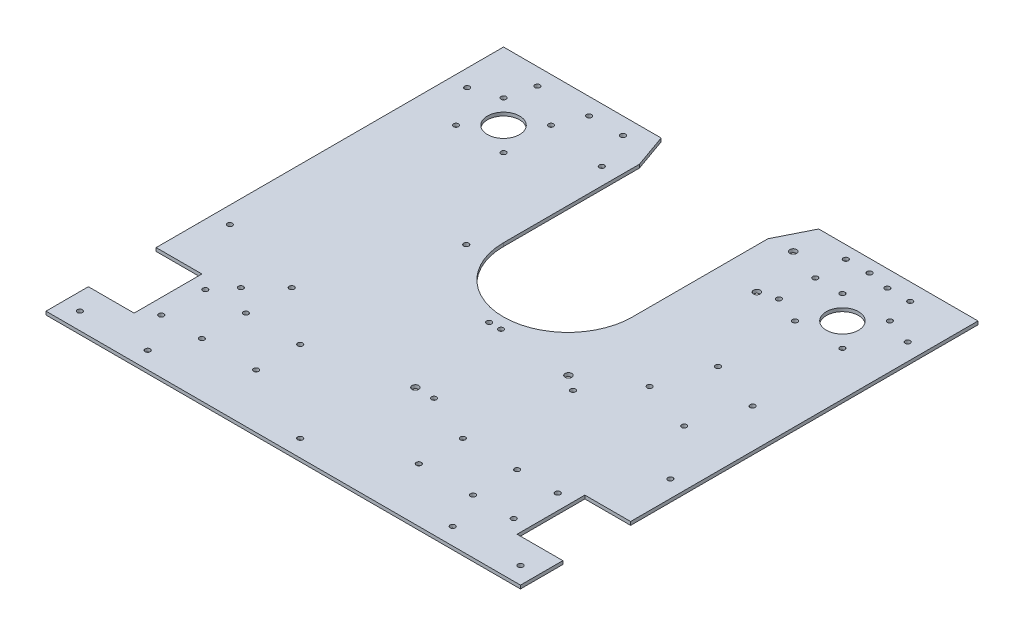
SolidWorks part; units mm, degrees
ref_plane "Plan de face" through (0, 0, 0) normal (0, 0, 1) x (1, 0, 0)
ref_plane "Plan de dessus" through (0, 0, 0) normal (0, 1, 0) x (1, 0, 0)
ref_plane "Plan de droite" through (0, 0, 0) normal (1, 0, 0) x (0, 0, -1)
sketch "Esquisse1" plane through (0, 0, 0) normal (0, 1, 0) x (1, 0, 0)
  line L0 (215.2266, 224.3116) -> (-64.7734, 224.3116)
  line L1 (-64.7734, 224.3116) -> (-64.7734, 19.3116)
  line L2 (-64.7734, 19.3116) -> (-37.7734, 19.3116)
  line L3 (-37.7734, 19.3116) -> (-37.7734, -20.6884)
  line L4 (-37.7734, -20.6884) -> (-64.7734, -20.6884)
  line L5 (-64.7734, -20.6884) -> (-64.7734, -45.6884)
  line L6 (-64.7734, -45.6884) -> (215.2266, -45.6884)
  line L7 (215.2266, -45.6884) -> (215.2266, -20.6884)
  line L8 (215.2266, -20.6884) -> (188.2266, -20.6884)
  line L9 (188.2266, -20.6884) -> (188.2266, 19.3116)
  line L10 (188.2266, 19.3116) -> (215.2266, 19.3116)
  line L11 (215.2266, 19.3116) -> (215.2266, 224.3116)
  line L12 (3.9048, -0.6884) -> (149.2216, -0.6884) construction
  line L13 (75.2266, -25.6884) -> (75.2266, 10.3116) construction
  circle A0 centre (27.2266, 12.3116) radius 1.5
  circle A1 centre (27.2266, -13.6884) radius 1.5
  circle A2 centre (123.2266, -13.6884) radius 1.5
  circle A3 centre (-54.7734, -35.6884) radius 1.5
  circle A4 centre (205.2266, -35.6884) radius 1.5
  circle A5 centre (-28.7734, 12.3116) radius 1.5
  circle A6 centre (-28.7734, -13.6884) radius 1.5
  circle A7 centre (-4.7734, 12.3116) radius 1.5
  circle A8 centre (-4.7734, -13.6884) radius 1.5
  circle A9 centre (165.2266, -35.6884) radius 1.5
  circle A11 centre (155.2266, -13.6884) radius 1.5
  circle A12 centre (155.2266, 12.3116) radius 1.5
  circle A13 centre (179.2266, -13.6884) radius 1.5
  circle A14 centre (179.2266, 12.3116) radius 1.5
  circle A15 centre (-24.7734, 184.3116) radius 9.5
  circle A16 centre (-38.7734, 198.3116) radius 1.5
  circle A17 centre (-10.7734, 170.3116) radius 1.5
  circle A18 centre (-38.7734, 170.3116) radius 1.5
  circle A19 centre (-10.7734, 198.3116) radius 1.5
  circle A20 centre (161.2266, 198.3116) radius 1.5
  circle A21 centre (189.2266, 170.3116) radius 1.5
  circle A22 centre (161.2266, 170.3116) radius 1.5
  circle A23 centre (189.2266, 198.3116) radius 1.5
  circle A24 centre (175.2266, 184.3116) radius 9.5
  circle A25 centre (-14.7734, -35.6884) radius 1.5
  circle A26 centre (75.2266, -35.6884) radius 1.5
  circle A28 centre (123.2266, 12.3116) radius 1.5
  dimension "D10" = 65
  dimension "D12" = 13
  dimension "D13" = 10
  dimension "D17" = 9
  dimension "D18" = 13
  dimension "D20" = 24
  dimension "D22" = 40
  dimension "D24" = 14
  dimension "D26" = 14
  dimension "D28" = 27
  dimension "D29" = 50
  dimension "D11" = 13
  dimension "D2" = 280
  dimension "D3" = 270
  dimension "D4" = 27
  dimension "D5" = 27
  dimension "D6" = 40
  dimension "D7" = 40
  dimension "D8" = 25
  dimension "D9" = 25
  dimension "D14" = 10
  dimension "D16" = 20
  dimension "D19" = 13
  dimension "D23" = 40
  dimension "D25" = 14
  dimension "D27" = 14
  dimension "D31" = 140
  dimension "D32" = 9
  dimension "D33" = 24
  dimension "D34" = 65
  dimension "D35" = 27
  dimension "D36" = 140
extrude "Extrusion1" add sketch "Esquisse1" along normal blind 2
sketch "Esquisse3" plane through (0, 2, 0) normal (0, 1, 0) x (-1, 0, 0)
  line L2 (-35.2266, -224.3116) -> (-35.2266, -124.3116)
  line L3 (-215.2266, -224.3116) -> (64.7734, -224.3116) construction
  line L4 (-111.2266, -224.3116) -> (-111.2266, -124.3116)
  line L6 (-73.2266, -168.757) -> (-73.2266, -124.3116) construction
  line L8 (-35.2266, -224.3116) -> (-111.2266, -224.3116)
  line L9 (64.7734, -224.3116) -> (64.7734, -19.3116) construction
  arc A0 (-35.2266, -124.3116) -> (-111.2266, -124.3116) centre (-73.2266, -124.3116) ccw
  dimension "D1" = 38
  dimension "D3" = 100
  dimension "D2" = 100
extrude "Extrusion3" cut sketch "Esquisse3" against normal through all
sketch "Esquisse4" plane through (0, 0, 0) normal (0, -1, 0) x (1, 0, 0)
  line L0 (-54.7734, -214.3116) -> (-54.7734, -30.4654) construction
  line L1 (-64.7734, -224.3116) -> (-64.7734, -19.3116) construction
  line L2 (35.2266, -224.3116) -> (-64.7734, -224.3116) construction
  line L3 (111.2266, -124.3116) -> (111.2266, -224.3116) construction
  line L4 (215.2266, -19.3116) -> (215.2266, -224.3116) construction
  line L5 (205.2266, -214.3116) -> (205.2266, -30.4654) construction
  line L6 (-54.7734, -214.3116) -> (25.7266, -214.3116) construction
  line L7 (205.2266, -214.3116) -> (160.2266, -214.3116) construction
  line L8 (25.2266, -192.3116) -> (25.2266, -112.3116) construction
  line L9 (35.2266, -224.3116) -> (35.2266, -124.3116) construction
  line L10 (145.2266, -198.3116) -> (145.2266, -176.8116) construction
  line L11 (158.7266, -216.8116) -> (144.7266, -216.8116) construction
  line L12 (215.2266, -224.3116) -> (111.2266, -224.3116) construction
  line L13 (145.2266, -198.3116) -> (135.2266, -198.3116) construction
  circle A0 centre (-54.7734, -192.8116) radius 1.5
  circle A1 centre (-54.7734, -52.8116) radius 1.5
  circle A2 centre (205.2266, -52.8116) radius 1.5
  circle A3 centre (205.2266, -192.8116) radius 1.5
  circle A4 centre (-34.7734, -214.3116) radius 1.5
  circle A5 centre (-4.2734, -214.3116) radius 1.5
  circle A6 centre (171.7266, -214.3116) radius 1.5
  circle A7 centre (185.2266, -214.3116) radius 1.5
  circle A8 centre (15.7266, -214.3116) radius 1.5
  circle A9 centre (158.7266, -216.8116) radius 1.5
  circle A10 centre (25.2266, -192.3116) radius 1.5
  circle A11 centre (25.2266, -112.3116) radius 1.5
  circle A12 centre (144.7266, -216.8116) radius 1.5
  circle A13 centre (125.2266, -205.3116) radius 2
  circle A14 centre (145.2266, -176.8116) radius 1.5
  circle A15 centre (145.2266, -198.3116) radius 1.5
  circle A16 centre (135.2266, -173.8116) radius 2
  dimension "D2" = 31.5
  dimension "D5" = 80.5
  dimension "D6" = 30
  dimension "D8" = 10
  dimension "D9" = 80
  dimension "D13" = 7.5
  dimension "D15" = 33.5
  dimension "D16" = 14
  dimension "D18" = 30
  dimension "D21" = 10
  dimension "D20" = 18.5
  dimension "D23" = 21.5
  dimension "D24" = 3
  dimension "D1" = 10
  dimension "D3" = 140
  dimension "D4" = 10
  dimension "D7" = 30
  dimension "D10" = 22
  dimension "D11" = 10
  dimension "D12" = 45
  dimension "D14" = 10
  dimension "D17" = 14
  dimension "D19" = 13.5
  dimension "D22" = 10
  dimension "D25" = 10
  dimension "D26" = 31.5
  dimension "D27" = 140
extrude "Extrusion4" cut sketch "Esquisse4" against normal blind 10
sketch "Esquisse5" plane through (0, 2, 0) normal (0, 1, 0) x (-1, 0, 0)
  line L0 (-215.2266, -19.3116) -> (-215.2266, -224.3116) construction
  line L1 (-215.2266, -224.3116) -> (-111.2266, -224.3116) construction
  line L5 (-151.8292, -93.9142) -> (-161.8292, -124.3116) construction
  line L6 (-151.8292, -93.9142) -> (-182.2266, -83.9142) construction
  line L7 (-182.2266, -83.9142) -> (-192.2266, -114.3116) construction
  line L8 (-161.8292, -124.3116) -> (-192.2266, -114.3116) construction
  line L12 (-111.2266, -124.3116) -> (-111.2266, -224.3116) construction
  circle A0 centre (-131.2266, -69.3116) radius 1.5
  circle A1 centre (-131.2266, -69.3116) radius 11 construction
  circle A2 centre (-122.2266, -75.6362) radius 2
  circle A3 centre (-151.8292, -93.9142) radius 1.5
  circle A5 centre (-161.8292, -124.3116) radius 1.5
  circle A6 centre (-94.2266, -24.3116) radius 11 construction
  circle A7 centre (-83.2266, -24.3116) radius 2
  circle A10 centre (-94.2266, -24.3116) radius 1.5
  circle A16 centre (-192.2266, -114.3116) radius 1.5
  circle A17 centre (-182.2266, -83.9142) radius 1.5
  dimension "D5" = 9
  dimension "D6" = 23
  dimension "D7" = 20
  dimension "D9" = 0
  dimension "D10" = 17
  dimension "D15" = 32
  dimension "D4" = 22
  dimension "D20" = 32
  dimension "D3" = 100
  dimension "D13" = 22
  dimension "D11" = 33
  dimension "D8" = 155
  dimension "D14" = 200
extrude "Extrusion5" cut sketch "Esquisse5" against normal blind 10
sketch "Esquisse6" plane through (0, 2, 0) normal (0, 1, 0) x (-1, 0, 0)
  line L0 (-28.2266, -224.3116) -> (-38.2266, -224.3116)
  line L1 (-35.2266, -224.3116) -> (64.7734, -224.3116) construction
  line L2 (-38.2266, -224.3116) -> (-35.2266, -204.5379)
  line L3 (-35.2266, -224.3116) -> (-35.2266, -124.3116) construction
  line L4 (-35.2266, -204.5379) -> (-28.2266, -224.3116)
  line L5 (-111.2266, -224.3116) -> (-121.2266, -224.3116)
  line L6 (-215.2266, -224.3116) -> (-111.2266, -224.3116) construction
  line L7 (-121.2266, -224.3116) -> (-111.2266, -204.3116)
  line L8 (-111.2266, -124.3116) -> (-111.2266, -224.3116) construction
  line L9 (-111.2266, -204.3116) -> (-111.2266, -224.3116)
  dimension "D1" = 10
  dimension "D2" = 20
  dimension "D3" = 20
  dimension "D4" = 10
extrude "Extrusion6" cut sketch "Esquisse6" against normal blind 10
sketch "Esquisse7" plane through (0, 2, 0) normal (0, 1, 0) x (-1, 0, 0)
  line L0 (-71.7266, -79.3116) -> (-78.7266, -79.3116) construction
  line L1 (-75.2266, -79.3116) -> (-75.2266, -79.0099) construction
  line L2 (64.7734, -224.3116) -> (64.7734, -19.3116) construction
  circle A0 centre (-71.7266, -79.3116) radius 1.5
  circle A1 centre (-78.7266, -79.3116) radius 1.5
  arc A2 (-35.2266, -124.3116) -> (-111.2266, -124.3116) centre (-73.2266, -124.3116) ccw construction
  dimension "D1" = 7
  dimension "D2" = 140
  dimension "D3" = 45
extrude "Extrusion7" cut sketch "Esquisse7" against normal blind 10
sketch "Esquisse8" plane through (0, 2, 0) normal (0, 1, 0) x (-1, 0, 0)
  line L0 (64.7734, -224.3116) -> (64.7734, -19.3116) construction
  line L1 (-28.2266, -224.3116) -> (64.7734, -224.3116) construction
  circle A0 centre (19.2734, -23.8116) radius 1.5
  circle A1 centre (4.2734, -38.8116) radius 1.5
  dimension "D1" = 15
  dimension "D2" = 15
  dimension "D3" = 45.5
  dimension "D4" = 200.5
extrude "Extrusion8" cut sketch "Esquisse8" against normal blind 10
